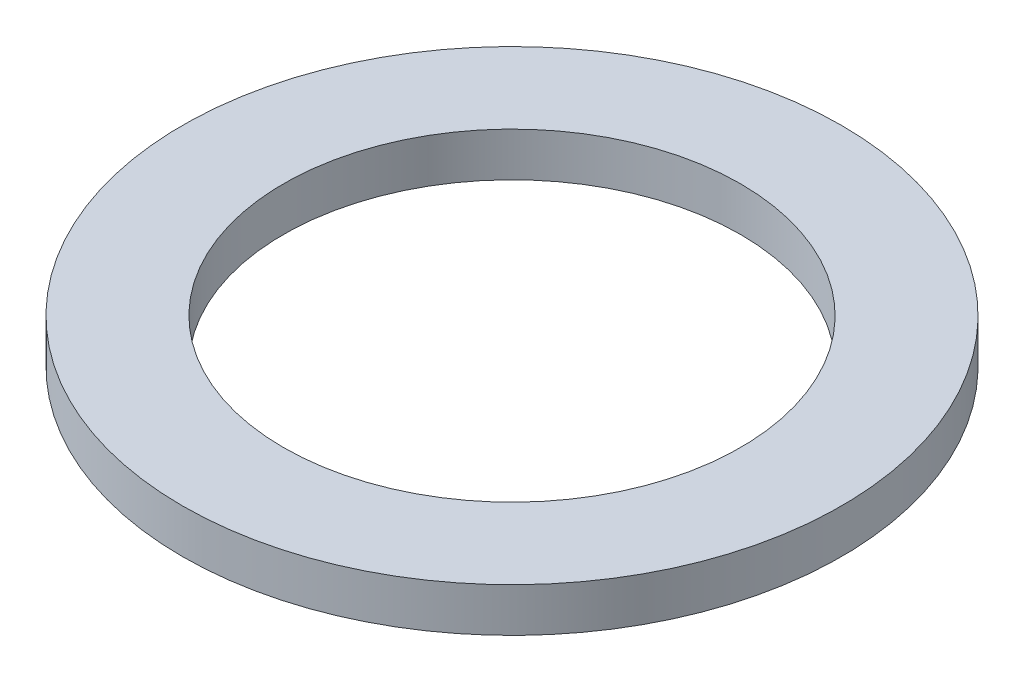
SolidWorks part; units mm, degrees
material "Thornel Mat VMA"
ref_plane "前视基准面" through (0, 0, 0) normal (0, 0, 1) x (1, 0, 0)
ref_plane "上视基准面" through (0, 0, 0) normal (0, 1, 0) x (1, 0, 0)
ref_plane "右视基准面" through (0, 0, 0) normal (1, 0, 0) x (0, 0, -1)
sketch "草图1" plane through (0, 0, 0) normal (0, 1, 0) x (1, 0, 0)
  circle A0 centre (0, 0) radius 5.2
  circle A1 centre (0, 0) radius 7.5
  dimension "D1" = 10.4
  dimension "D2" = 15
extrude "凸台-拉伸1" add sketch "草图1" along normal blind 1
